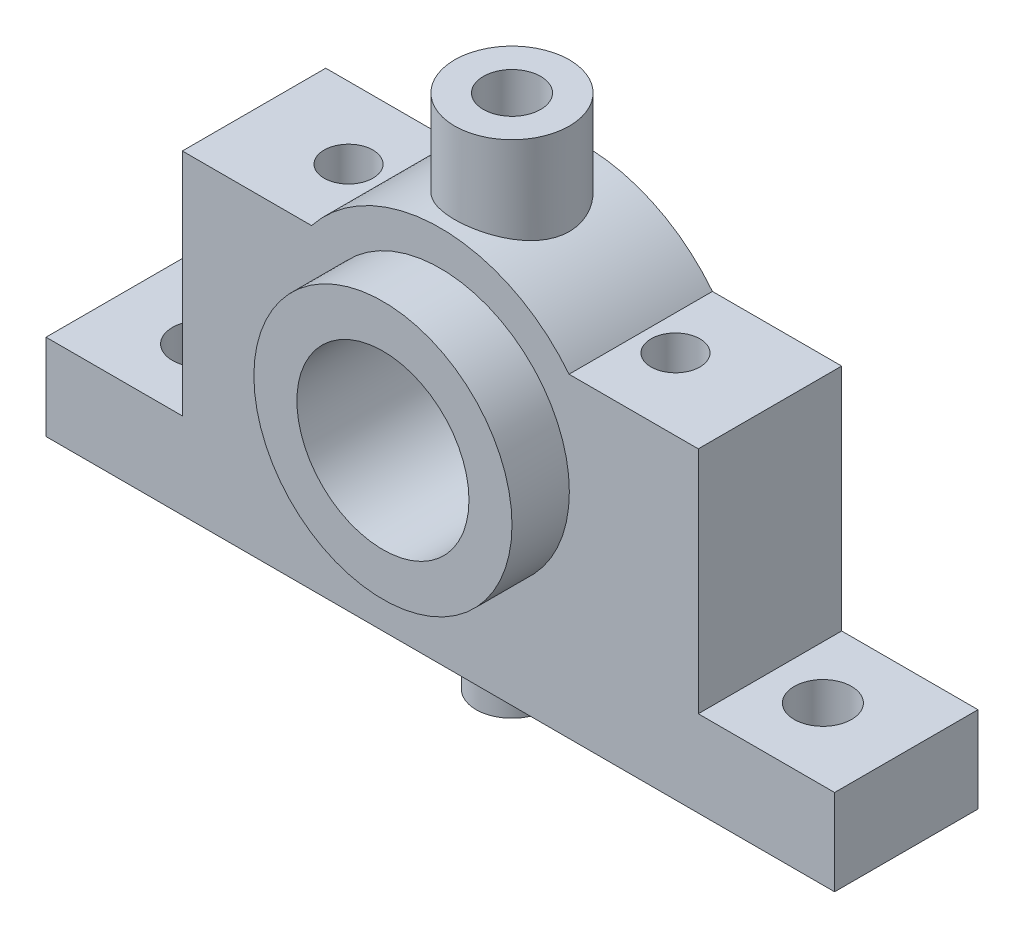
SolidWorks part; units mm, degrees
ref_plane "Front Plane" through (0, 0, 0) normal (0, 0, 1) x (1, 0, 0)
ref_plane "Top Plane" through (0, 0, 0) normal (0, 1, 0) x (1, 0, 0)
ref_plane "Right Plane" through (0, 0, 0) normal (1, 0, 0) x (0, 0, -1)
sketch "Sketch2" plane through (0, 0, 0) normal (0, 0, 1) x (1, 0, 0)
  line L0 (43.6499, 0) -> (-43.6499, 0)
  line L1 (-43.6499, 0) -> (-43.6499, 9.525)
  line L2 (-43.6499, 9.525) -> (-28.5572, 9.525)
  line L3 (-28.5572, 9.525) -> (-28.5572, 34.925)
  line L4 (-28.5572, 34.925) -> (-14.2516, 34.925)
  line L5 (0, 0) -> (0, 45.2868) construction
  line L6 (28.5572, 34.925) -> (14.2516, 34.925)
  line L7 (28.5572, 9.525) -> (28.5572, 34.925)
  line L8 (43.6499, 9.525) -> (28.5572, 9.525)
  line L9 (43.6499, 0) -> (43.6499, 9.525)
  circle A0 centre (0, 23.6728) radius 14.2875
  arc A2 (14.2516, 34.925) -> (-14.2516, 34.925) centre (0, 23.6728) ccw
  dimension "D4" = 23.6728
  dimension "D1" = 87.2998
  dimension "D2" = 9.525
  dimension "D3" = 34.925
extrude "Boss-Extrude1" add sketch "Sketch2" along normal mid plane 15.875
sketch "Sketch4" plane through (0, 0, 0) normal (0, 0, 1) x (1, 0, 0)
  circle A0 centre (0, 23.6728) radius 14.2875 construction
  circle A1 centre (0, 23.6728) radius 14.2875
  circle A2 centre (0, 23.6728) radius 9.525
extrude "Boss-Extrude2" add sketch "Sketch4" along normal blind 14.2875 and the other way blind 11.1125
sketch "Sketch5" plane through (0, 0, 0) normal (0, -1, 0) x (1, 0, 0)
  circle A0 centre (0, 0) radius 3.9688
extrude "Boss-Extrude3" add sketch "Sketch5" along normal blind 6.35
ref_plane "Plane1" through (0, 38.1, 0) normal (0, 1, 0) x (1, 0, 0)
sketch "Sketch6" plane through (0, 38.1, 0) normal (0, 1, 0) x (1, 0, 0)
  circle A0 centre (0, 0) radius 6.35
extrude "Boss-Extrude4" add sketch "Sketch6" along normal blind 12.7
sketch "Sketch7" plane through (0, 9.525, 0) normal (0, 1, 0) x (1, 0, 0)
  line L0 (0, -55) -> (0, 55) construction
  circle A0 centre (34.417, 0) radius 3.175
  circle A1 centre (-34.417, 0) radius 3.175
  dimension "D1" = 34.417
  dimension "D2" = 68.834
extrude "Cut-Extrude1" cut sketch "Sketch7" against normal blind 19.05
hole_wizard "1/4-28 Tapped Hole1" positions "3DSketch6" profile "Sketch11" tap size "1/4-28" standard "ANSI Inch"
sketch3d "3DSketch6"
  line L0 (-14.2516, 34.925, -7.9375) -> (-28.5572, 34.925, -7.9375) construction
  point P0 (-18.0975, 34.925, 0)
  point P3 (18.0975, 34.925, 0)
  dimension "D1" = 36.195
  dimension "D2" = 7.9375
sketch "Sketch11" plane through (-18.0975, 34.925, 0) normal (1, 0, 0) x (0, 0, 1)
  line L0 (0, 0) -> (0, 27.0254)
  line L1 (0, 27.0254) -> (2.7051, 25.4)
  line L2 (2.7051, 25.4) -> (2.7051, 0)
  line L5 (2.7051, 0) -> (0, 0)
  line L10 (0, 27.0254) -> (-2.7051, 25.4) construction
  line L11 (0, -6.35) -> (0, 107.95) construction
  dimension "Tap Drill Dia." = 5.4102
  dimension "Tap Drill Depth" = 25.4
  dimension "Drill Angle" = 118
cosmetic thread "Hole Thread1" parameters "D1"=12.7, "D2"=6.35
cosmetic thread "Hole Thread2" parameters "D1"=12.7, "D2"=6.35
hole_wizard "1/4 (0.25) Diameter Hole1" positions "Sketch12" profile "Sketch13" hole size "1/4" standard "ANSI Inch"
sketch "Sketch12" plane through (0, 50.8, 0) normal (0, 1, 0) x (1, 0, 0)
  point P0 (0, 0)
sketch "Sketch13" plane through (0, 50.8, 0) normal (1, 0, 0) x (0, 0, 1)
  line L0 (0, 0) -> (0, 14.6077)
  line L1 (0, 14.6077) -> (3.175, 12.7)
  line L2 (3.175, 12.7) -> (3.175, 0)
  line L5 (3.175, 0) -> (0, 0)
  line L10 (0, 14.6077) -> (-3.175, 12.7) construction
  line L11 (0, -6.35) -> (0, 107.95) construction
  dimension "Hole Dia." = 6.35
  dimension "Hole Depth" = 12.7
  dimension "Drill Angle" = 118
sketch "Sketch19" plane through (0, 0, 0) normal (0, 0, 1) x (1, 0, 0)
  line L0 (0, 36.202) -> (0, 23.6728) construction
sketch "Sketch21" plane through (0, 50.8, 0) normal (0, 1, 0) x (1, 0, 0)
  circle A0 centre (0, 0) radius 0.508
extrude "Cut-Extrude2" cut sketch "Sketch21" against normal blind 19.05
sketch "Sketch22" plane through (0, 0, -11.1125) normal (0, 0, -1) x (-1, 0, 0)
  circle A0 centre (0, 23.6728) radius 9.525 construction
  circle A1 centre (0, 23.6728) radius 9.525
  circle A2 centre (0, 23.6728) radius 14.2875 construction
  circle A3 centre (0, 23.6728) radius 14.2875
extrude "Cut-Extrude3" cut sketch "Sketch22" against normal up to vertex (1.5875 mm away)
